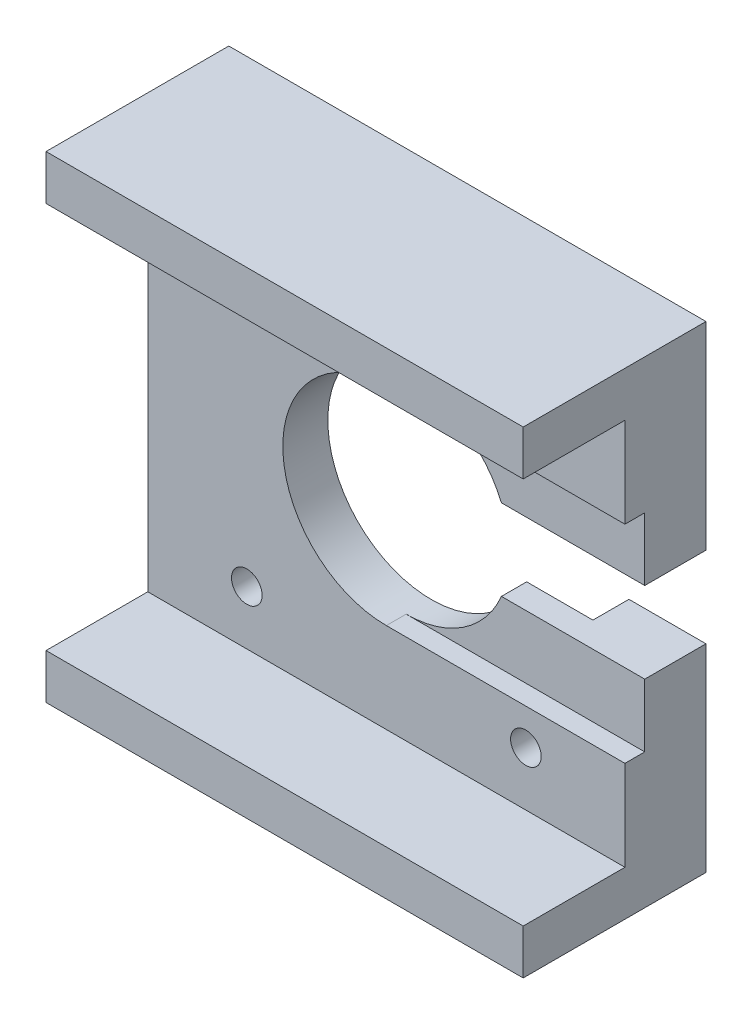
SolidWorks part; units mm, degrees
ref_plane "Front Plane" through (0, 0, 0) normal (0, 0, 1) x (1, 0, 0)
ref_plane "Top Plane" through (0, 0, 0) normal (0, 1, 0) x (1, 0, 0)
ref_plane "Right Plane" through (0, 0, 0) normal (1, 0, 0) x (0, 0, -1)
sketch "Sketch1" plane through (0, 0, 0) normal (0, 0, 1) x (1, 0, 0)
  line L1 (-21.5, -21.5) -> (21.5, -21.5) construction
  line L2 (-21.5, -21.5) -> (-21.5, 21.5) construction
  line L3 (-21.5, 21.5) -> (21.5, 21.5) construction
  line L4 (21.5, -21.5) -> (21.5, 21.5) construction
  line L5 (-21.5, -21.5) -> (21.5, 21.5) construction
  line L6 (-21.5, 21.5) -> (21.5, -21.5) construction
  line L7 (-26.5, 26.5) -> (26.5, 26.5)
  line L8 (-26.5, 26.5) -> (-26.5, -26.5)
  line L9 (-26.5, -26.5) -> (26.5, -26.5)
  line L10 (26.5, 26.5) -> (26.5, -26.5)
  line L11 (-26.5, 26.5) -> (26.5, -26.5) construction
  line L12 (-26.5, -26.5) -> (26.5, 26.5) construction
  point P0 (0, 0)
  point P6 (0, 0)
  dimension "D1" = 43
  dimension "D2" = 43
  dimension "D3" = 5
  dimension "D4" = 5
extrude "Boss-Extrude1" add sketch "Sketch1" along normal blind 5
sketch "Sketch2" plane through (0, 0, 5) normal (0, 0, 1) x (1, 0, 0)
  line L0 (-21.5, 21.5) -> (-26.5, 21.5)
  line L1 (-21.5, 21.5) -> (21.5, 21.5)
  line L2 (-21.5, 21.5) -> (-21.5, -21.5)
  line L3 (-21.5, -21.5) -> (21.5, -21.5)
  line L4 (21.5, 21.5) -> (21.5, -21.5)
  line L5 (-21.5, 21.5) -> (21.5, -21.5) construction
  line L6 (-21.5, -21.5) -> (21.5, 21.5) construction
  line L7 (-26.5, -26.5) -> (26.5, -26.5)
  line L8 (-26.5, -26.5) -> (-26.5, 26.5)
  line L9 (-26.5, 26.5) -> (26.5, 26.5)
  line L10 (26.5, -26.5) -> (26.5, 26.5)
  line L11 (-26.5, -26.5) -> (26.5, 26.5) construction
  line L12 (-26.5, 26.5) -> (26.5, -26.5) construction
  line L13 (21.5, 21.5) -> (26.5, 21.5)
  line L14 (-21.5, -21.5) -> (-26.5, -21.5)
  line L15 (21.5, -21.5) -> (26.5, -21.5)
  point P0 (0, 0)
  point P6 (0, 0)
  line M9 (26.5, -26.5) -> (26.5, 26.5)
  line M10 (26.5, 26.5) -> (-26.5, 26.5)
  line M11 (-26.5, 26.5) -> (-26.5, -26.5)
  line M12 (-26.5, -26.5) -> (26.5, -26.5)
  dimension "D1" = 43
  dimension "D2" = 43
extrude "Boss-Extrude2" add sketch "Sketch2" along normal blind 11.3 contours L1 L13 L10 L0 M10 M11 | L15 L3 L14 L8 M12 M9
sketch "Sketch4" plane through (0, 0, 5) normal (0, 0, 1) x (1, 0, 0)
  line L1 (26.5, -21.5) -> (26.5, 21.5) construction
  line L2 (5.5, 4.5) -> (26.5, 4.5)
  line L3 (5.5, 4.5) -> (5.5, -4.5)
  line L4 (5.5, -4.5) -> (26.5, -4.5)
  line L5 (26.5, 4.5) -> (26.5, -4.5)
  line L6 (5.5, 4.5) -> (26.5, -4.5) construction
  line L7 (5.5, -4.5) -> (26.5, 4.5) construction
  circle A0 centre (0, 0) radius 11.5
  point P3 (16, 0)
  line M3 (26.5, -21.5) -> (26.5, 21.5)
  dimension "D1" = 23
  dimension "D2" = 9
  dimension "D3" = 21
extrude "Cut-Extrude1" cut sketch "Sketch4" against normal through all contours A0 L4 L2 M3 | L4 A0 L2 L3 | L2 A0 L4 L3
sketch "Sketch3" plane through (0, 0, 5) normal (0, 0, 1) x (1, 0, 0)
  line L0 (-26.5, 11.5) -> (26.5, 11.5)
  line L1 (-26.5, 21.5) -> (-26.5, -21.5) construction
  line L2 (26.5, -21.5) -> (26.5, -4.5) construction
  line L3 (-26.5, -11.5) -> (26.5, -11.5)
  line L4 (-26.5, 11.5) -> (-26.5, -11.5)
  line L5 (26.5, 11.5) -> (26.5, -11.5) construction
  circle A0 centre (0, 0) radius 11.5
  line M4 (26.5, -21.5) -> (26.5, -4.5)
  arc M10 (10.583, -4.5) -> (10.583, 4.5) centre (0, 0) cw
  line M11 (10.583, 4.5) -> (26.5, 4.5)
  line M12 (26.5, 4.5) -> (26.5, 21.5)
  line M13 (26.5, -4.5) -> (10.583, -4.5)
  dimension "D1" = 23
extrude "Cut-Extrude2" cut sketch "Sketch3" against normal blind 2.2 contours A0 M11 M13 M10 | A0 L0 M11 M12 | A0 L3 M4 M13
sketch "Sketch5" plane through (0, 0, 0) normal (0, 0, -1) x (-1, 0, 0)
  line L1 (-15.5, 15.5) -> (15.5, 15.5) construction
  line L2 (-15.5, 15.5) -> (-15.5, -15.5) construction
  line L3 (-15.5, -15.5) -> (15.5, -15.5) construction
  line L4 (15.5, 15.5) -> (15.5, -15.5) construction
  line L5 (-15.5, 15.5) -> (15.5, -15.5) construction
  line L6 (-15.5, -15.5) -> (15.5, 15.5) construction
  circle A0 centre (-15.5, 15.5) radius 1.7
  point P0 (0, 0)
  dimension "D3" = 3.4
  dimension "D1" = 31
  dimension "D2" = 31
extrude "Cut-Extrude3" cut sketch "Sketch5" against normal through all
pattern_circular "CirPattern1" count 4 over 360 about axis through (0, 0, 0) along (0, 0, 1) of "Cut-Extrude3"
sketch "Sketch6" plane through (0, 0, 0) normal (0, 0, -1) x (-1, 0, 0)
  line L1 (-26.5, 4.5) -> (-10.583, 4.5)
  line L2 (-26.5, 4.5) -> (-26.5, -4.5)
  line L3 (-26.5, -4.5) -> (-10.583, -4.5)
  line L4 (-10.583, 4.5) -> (-10.583, -4.5)
  line L5 (26.5, -26.5) -> (-26.5, -26.5)
  line L6 (26.5, -26.5) -> (26.5, 26.5)
  line L7 (26.5, 26.5) -> (-26.5, 26.5)
  line L8 (-26.5, -26.5) -> (-26.5, 26.5)
  circle A0 centre (0, 0) radius 11.5 construction
  circle A1 centre (-15.5, 15.5) radius 1.7
  circle A2 centre (15.5, 15.5) radius 1.7
  circle A3 centre (15.5, -15.5) radius 1.7
  circle A4 centre (-15.5, -15.5) radius 1.7
  circle A5 centre (0, 0) radius 18.5
  circle M11 centre (15.5, 15.5) radius 1.7
  circle M12 centre (15.5, -15.5) radius 1.7
  circle M13 centre (-15.5, -15.5) radius 1.7
  circle M14 centre (-15.5, 15.5) radius 1.7
  line M15 (-26.5, 4.5) -> (-10.583, 4.5)
  line M18 (-26.5, -4.5) -> (-26.5, -26.5)
  line M19 (-26.5, -26.5) -> (26.5, -26.5)
  line M20 (26.5, -26.5) -> (26.5, 26.5)
  line M21 (26.5, 26.5) -> (-26.5, 26.5)
  line M22 (-26.5, 26.5) -> (-26.5, 4.5)
  dimension "D1" = 3.4
  dimension "D2" = 3.4
  dimension "D3" = 3.4
  dimension "D4" = 3.4
  dimension "D5" = 23
  dimension "D6" = 37
extrude "Boss-Extrude3" add sketch "Sketch6" along normal blind 4 contours A5 L3 M18 M19 M20 M21 M22 M15 M12 M14 M13 M11
sketch "Sketch7" plane through (0, 0, -4) normal (0, 0, -1) x (-1, 0, 0)
  circle A0 centre (-15.5, 15.5) radius 2.95
  circle A1 centre (15.5, 15.5) radius 2.95
  circle A2 centre (15.5, -15.5) radius 2.95
  circle A3 centre (-15.5, -15.5) radius 2.95
  dimension "D1" = 5.9
  dimension "D2" = 5.9
  dimension "D3" = 5.9
  dimension "D4" = 5.9
extrude "Cut-Extrude4" cut sketch "Sketch7" against normal blind 0.5
